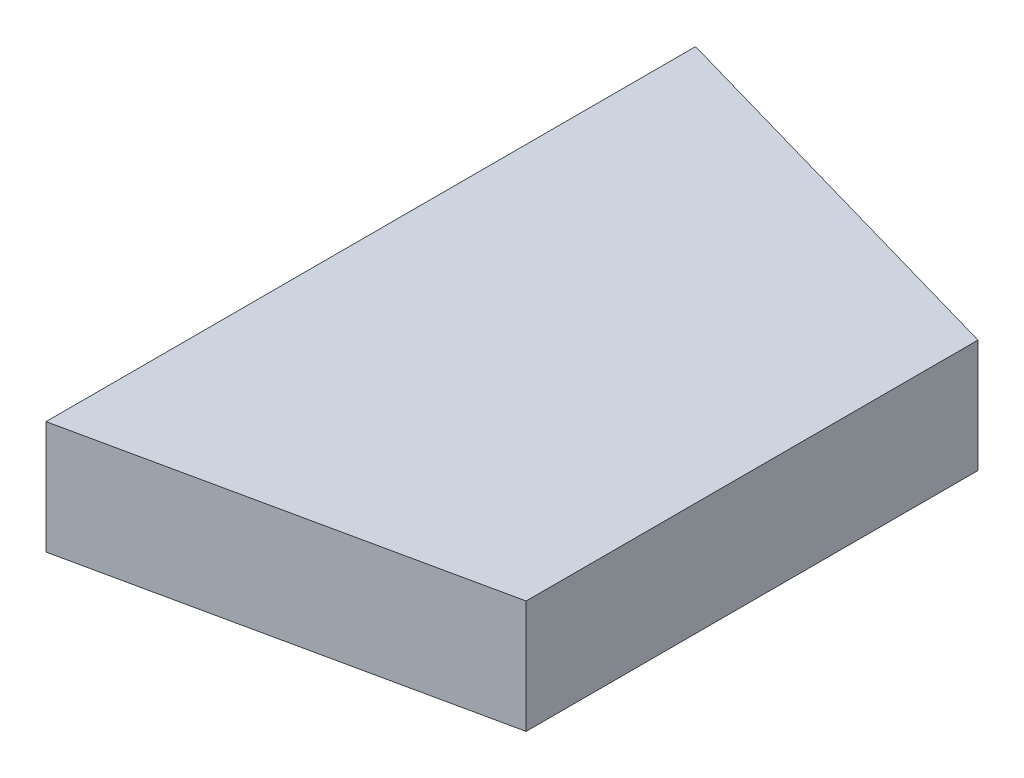
SolidWorks part; units mm, degrees
ref_plane "前视基准面" through (0, 0, 0) normal (0, 0, 1) x (1, 0, 0)
ref_plane "上视基准面" through (0, 0, 0) normal (0, 1, 0) x (1, 0, 0)
ref_plane "右视基准面" through (0, 0, 0) normal (1, 0, 0) x (0, 0, -1)
other "Configuration Table"
sketch "草图1" plane through (0, 0, 0) normal (0, 1, 0) x (1, 0, 0)
  line L0 (76, -66) -> (76, -20)
  line L1 (76, -20) -> (104, -28)
  line L2 (104, -28) -> (104, -60)
  line L3 (104, -60) -> (76, -66)
extrude "凸台-拉伸1" add sketch "草图1" along normal blind 8 from offset 4
sketch "草图2" plane through (0, 0, 0) normal (0, 1, 0) x (1, 0, 0)
  circle A0 centre (80, -62) radius 3
  circle A1 centre (80, -24) radius 3
  circle A2 centre (100, -50) radius 3
extrude "切除-拉伸1" cut sketch "草图2" against normal through all
